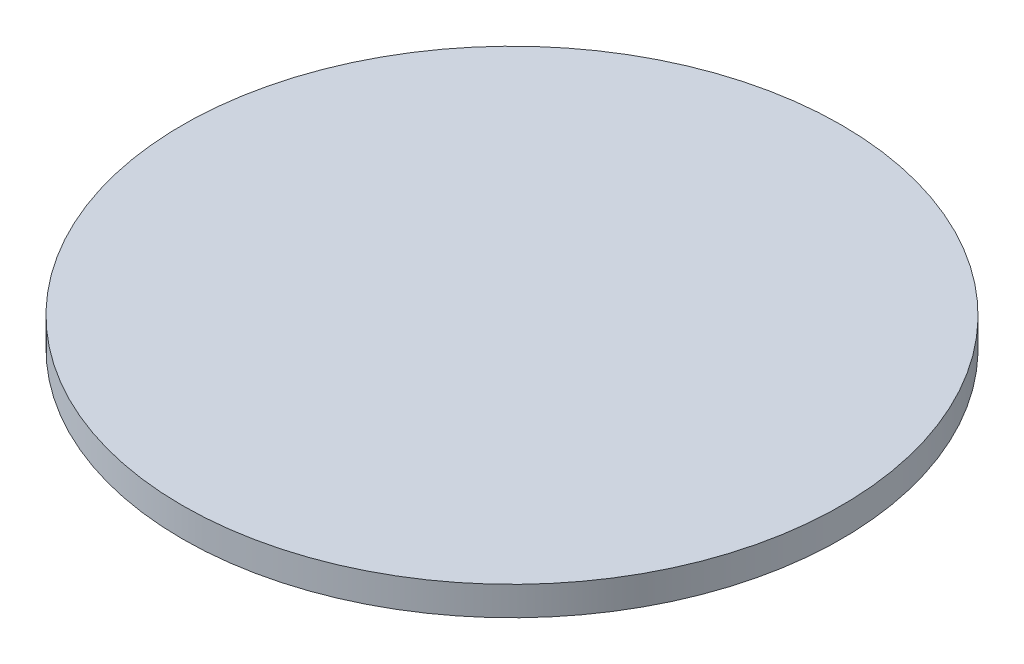
SolidWorks part; units mm, degrees
ref_plane "Front Plane" through (0, 0, 0) normal (0, 0, 1) x (1, 0, 0)
ref_plane "Top Plane" through (0, 0, 0) normal (0, 1, 0) x (1, 0, 0)
ref_plane "Right Plane" through (0, 0, 0) normal (1, 0, 0) x (0, 0, -1)
sketch "Sketch1" plane through (0, 0, 0) normal (0, 1, 0) x (1, 0, 0)
  circle A0 centre (0, 0) radius 45.5
  dimension "D1" = 91
extrude "Boss-Extrude1" add sketch "Sketch1" along normal blind 4
sketch "Sketch3" plane through (0, 0, 0) normal (0, -1, 0) x (1, 0, 0)
  circle A0 centre (0, 25) radius 3
  circle A1 centre (25, 0) radius 3
  circle A2 centre (0, -25) radius 3
  circle A3 centre (-25, 0) radius 3
  point P12 (0, 0)
  dimension "D1" = 6
  dimension "D2" = 25
  dimension "D3" = 4
extrude "Cut-Extrude1" cut sketch "Sketch3" against normal blind 3
